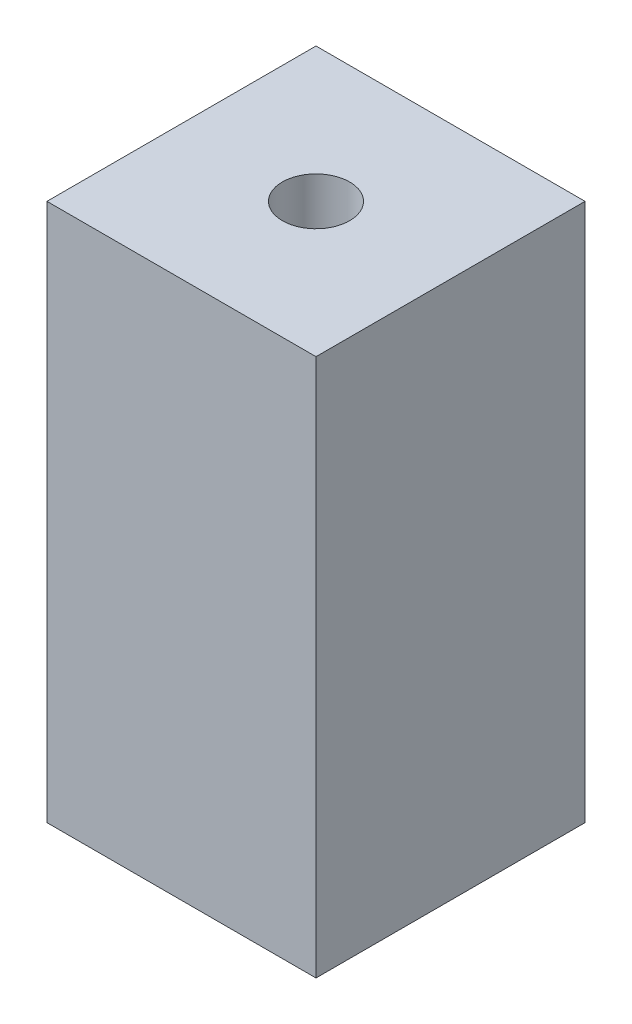
SolidWorks part; units mm, degrees
ref_plane "Front Plane" through (0, 0, 0) normal (0, 0, 1) x (1, 0, 0)
ref_plane "Top Plane" through (0, 0, 0) normal (0, 1, 0) x (1, 0, 0)
ref_plane "Right Plane" through (0, 0, 0) normal (1, 0, 0) x (0, 0, -1)
sketch "Sketch1" plane through (0, 0, 0) normal (0, 1, 0) x (1, 0, 0)
  line L1 (-25.4, -25.4) -> (25.4, -25.4)
  line L2 (-25.4, -25.4) -> (-25.4, 25.4)
  line L3 (-25.4, 25.4) -> (25.4, 25.4)
  line L4 (25.4, -25.4) -> (25.4, 25.4)
  line L5 (-25.4, -25.4) -> (25.4, 25.4) construction
  line L6 (-25.4, 25.4) -> (25.4, -25.4) construction
  point P0 (0, 0)
  dimension "D1" = 50.8
  dimension "D2" = 50.8
extrude "Boss-Extrude1" add sketch "Sketch1" along normal blind 101.6
sketch "Sketch2" plane through (0, 101.6, 0) normal (0, 1, 0) x (1, 0, 0)
  circle A0 centre (0, 0) radius 6.35
  dimension "D1" = 12.7
extrude "Cut-Extrude1" cut sketch "Sketch2" against normal blind 10
